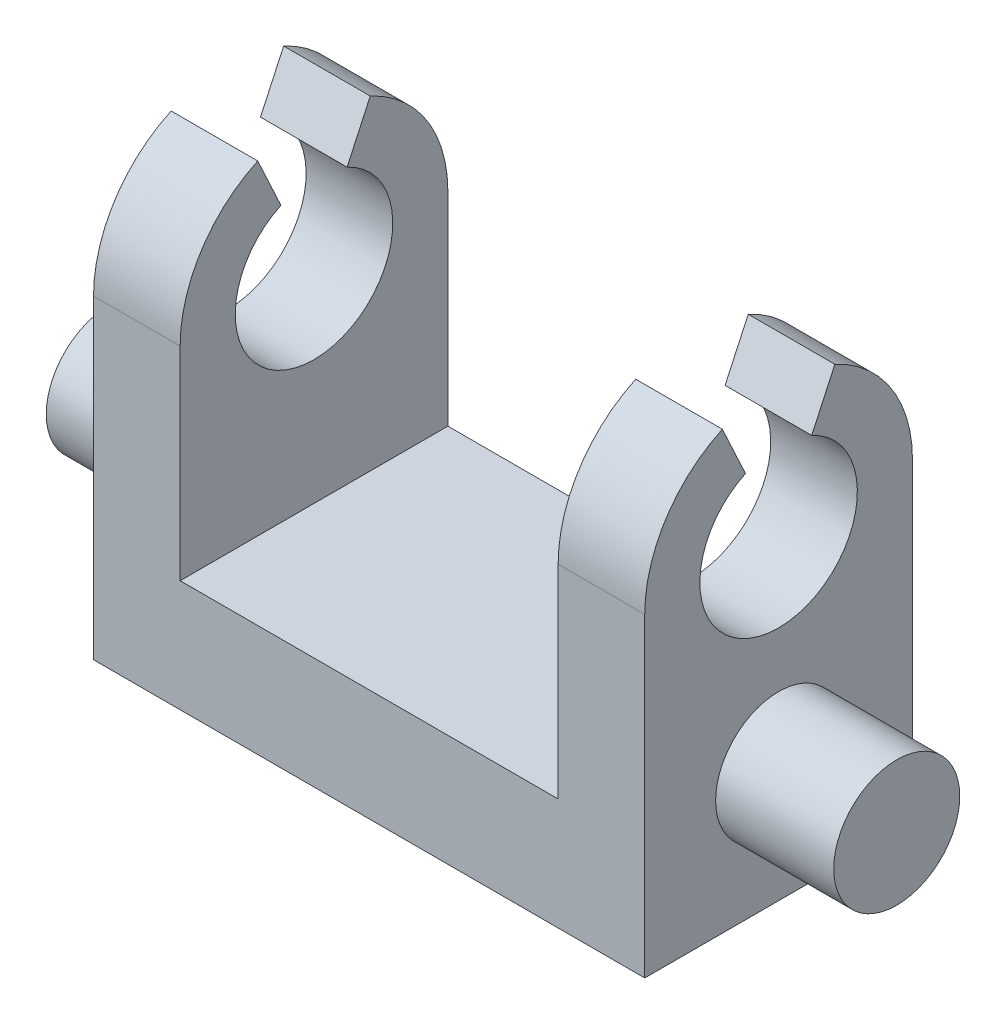
SolidWorks part; units mm, degrees
ref_plane "Front Plane" through (0, 0, 0) normal (0, 0, 1) x (1, 0, 0)
ref_plane "Top Plane" through (0, 0, 0) normal (0, 1, 0) x (1, 0, 0)
ref_plane "Right Plane" through (0, 0, 0) normal (1, 0, 0) x (0, 0, -1)
sketch "Sketch1" plane through (0, 0, 0) normal (1, 0, 0) x (0, 0, -1)
  circle A0 centre (0, 0) radius 8
  dimension "D1" = 16
extrude "Boss-Extrude1" add sketch "Sketch1" along normal mid plane 100
sketch "Sketch2" plane through (0, 0, 0) normal (1, 0, 0) x (0, 0, -1)
  line L2 (-17, 25) -> (-17, -15)
  line L3 (-17, -15) -> (17, -15)
  line L4 (17, 25) -> (17, -15)
  arc A0 (-17, 25) -> (17, 25) centre (0, 25) cw
  circle A1 centre (0, 25) radius 10
  dimension "D4" = 20
  dimension "D1" = 34
  dimension "D2" = 15
  dimension "D3" = 40
extrude "Boss-Extrude2" add sketch "Sketch2" along normal mid plane 70
sketch "Sketch3" plane through (0, 0, 0) normal (0, 0, 1) x (1, 0, 0)
  line L0 (35, 42) -> (-35, 42) construction
  line L1 (-24, 0) -> (24, 0)
  line L2 (-24, 0) -> (-24, 42)
  line L3 (-24, 42) -> (24, 42)
  line L4 (24, 0) -> (24, 42)
  dimension "D1" = 48
extrude "Cut-Extrude1" cut sketch "Sketch3" against normal mid plane 70
sketch "Sketch4" plane through (0, 0, -17) normal (0, 0, -1) x (-1, 0, 0)
  line L0 (-24, 0) -> (-24, 25) construction
  line L1 (-24, 0) -> (24, 0)
  line L2 (-24, 0) -> (-24, -0.81)
  line L3 (-24, -0.81) -> (24, -0.81)
  line L4 (24, 0) -> (24, -0.81)
  line L5 (24, 25) -> (24, 0) construction
  dimension "D1" = 0.81
extrude "Cut-Extrude2" cut sketch "Sketch4" against normal through all
sketch "Sketch5" plane through (-35, 0, 0) normal (-1, 0, 0) x (0, 0, 1)
  line L0 (-7.1444, 40.4259) -> (-4.2026, 34.074)
  line L1 (7.1444, 40.4259) -> (4.2026, 34.074)
  line L3 (-17, 25) -> (-17, -15)
  line L4 (-17, -15) -> (17, -15)
  line L5 (17, -15) -> (17, 25)
  circle A0 centre (0, 25) radius 10 construction
  arc A1 (17, 25) -> (-17, 25) centre (0, 25) ccw
  arc A2 (7.1444, 40.4259) -> (-7.1444, 40.4259) centre (0, 25) ccw
  arc A3 (4.2026, 34.074) -> (-4.2026, 34.074) centre (0, 25) ccw
  dimension "D1" = 0
extrude "Cut-Extrude3" cut sketch "Sketch5" against normal up to surface (70 mm away) up to face at (35, 0, 8)
